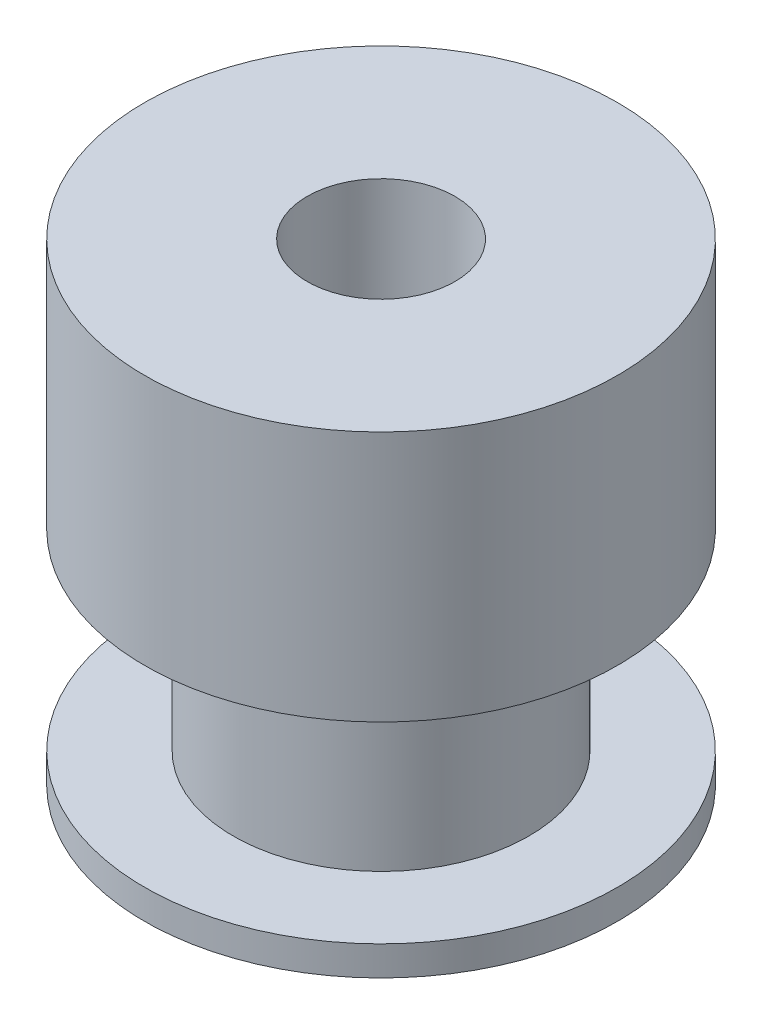
SolidWorks part; units mm, degrees
ref_plane "Front Plane" through (0, 0, 0) normal (0, 0, 1) x (1, 0, 0)
ref_plane "Top Plane" through (0, 0, 0) normal (0, 1, 0) x (1, 0, 0)
ref_plane "Right Plane" through (0, 0, 0) normal (1, 0, 0) x (0, 0, -1)
other "Default"
sketch "Sketch1" plane through (0, 0, 0) normal (0, 0, 1) x (1, 0, 0)
  line L0 (2.5, -8) -> (2.5, 8)
  line L1 (2.5, 8) -> (8, 8)
  line L2 (8, 8) -> (8, -0.5)
  line L3 (8, -0.5) -> (5, -0.5)
  line L4 (5, -0.5) -> (5, -7)
  line L5 (5, -7) -> (8, -7)
  line L6 (8, -7) -> (8, -8)
  line L7 (8, -8) -> (2.5, -8)
  line L8 (0, -4.8815) -> (0, 3.014) construction
  point P3 (2.5, 0)
  dimension "ID" = 5
  dimension "OD" = 16
  dimension "Length" = 16
  dimension "SlotSide" = 1
  dimension "SlotDiameter" = 10
  dimension "SlotLength" = 6.5
revolve "Revolve1" add sketch "Sketch1" angle 360 about L8
